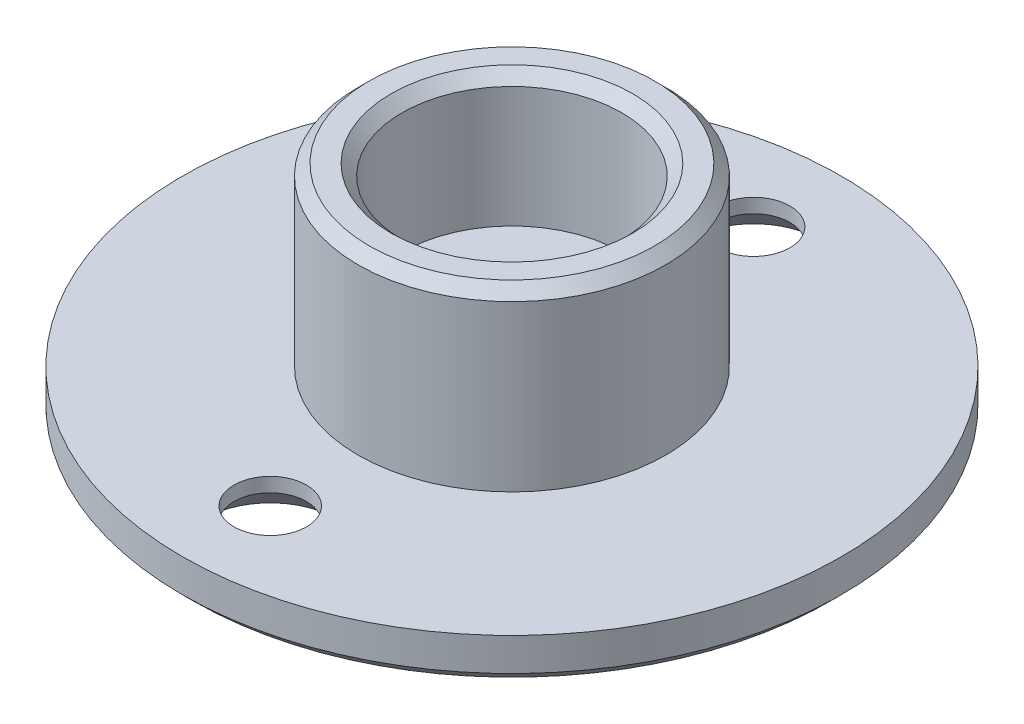
SolidWorks part; units mm, degrees
ref_plane "前视基准面" through (0, 0, 0) normal (0, 0, 1) x (1, 0, 0)
ref_plane "上视基准面" through (0, 0, 0) normal (0, 1, 0) x (1, 0, 0)
ref_plane "右视基准面" through (0, 0, 0) normal (1, 0, 0) x (0, 0, -1)
sketch "草图1" plane through (0, 0, 0) normal (0, 1, 0) x (1, 0, 0)
  circle A0 centre (0, 0) radius 15
  dimension "D1" = 30
extrude "凸台-拉伸1" add sketch "草图1" along normal blind 2
sketch "草图2" plane through (0, 2, 0) normal (0, 1, 0) x (1, 0, 0)
  circle A0 centre (0, 0) radius 7
  dimension "D1" = 14
extrude "凸台-拉伸2" add sketch "草图2" along normal blind 8
sketch "草图3" plane through (0, 10, 0) normal (0, 1, 0) x (1, 0, 0)
  circle A1 centre (0, 0) radius 5
  dimension "D1" = 10
extrude "切除-拉伸1" cut sketch "草图3" against normal blind 6
sketch "草图4" plane through (0, 4, 0) normal (0, 1, 0) x (1, 0, 0)
  circle A0 centre (0, 0) radius 3
  dimension "D1" = 6
extrude "切除-拉伸2" cut sketch "草图4" against normal through all
chamfer "倒角1" distance 0.5 angle 45 4 edges at (0, 10, 5) (0, 0, 15) (0, 10, 7) (0, 0, 3)
sketch "草图7" plane through (0, 0, 0) normal (0, 1, 0) x (1, 0, 0)
  circle A0 centre (0, 0) radius 11 construction
  circle A1 centre (0, -11) radius 1.9931 construction
  point P3 (0, -11)
  dimension "D1" = 22
hole_wizard "M6 内六角花形半沉头螺钉的锥形沉头孔1" positions "草图7" profile "草图8" countersink size "M6" standard "GB"
sketch "草图8" plane through (0, 0, 11) normal (1, 0, 0) x (0, 0, -1)
  line L0 (0, 0) -> (0, 3.65)
  line L1 (0, 3.65) -> (1.65, 2)
  line L2 (1.65, 2) -> (1.65, 1.35)
  line L3 (1.65, 1.35) -> (3, 0)
  line L5 (3, 0) -> (0, 0)
  line L6 (-1.65, 1.35) -> (-3, 0) construction
  line L10 (0, 3.65) -> (-1.65, 2) construction
  line L11 (0, -6.35) -> (0, 107.95) construction
  dimension "孔直径" = 3.3
  dimension "孔深度" = 2
  dimension "近端锥形沉头孔直径" = 6
  dimension "近端锥形沉头孔角度" = 90
  dimension "导头角度" = 90
mirror "镜向1" about plane through (0, 0, 0) normal (0, 0, 1) of "M6 内六角花形半沉头螺钉的锥形沉头孔1"
